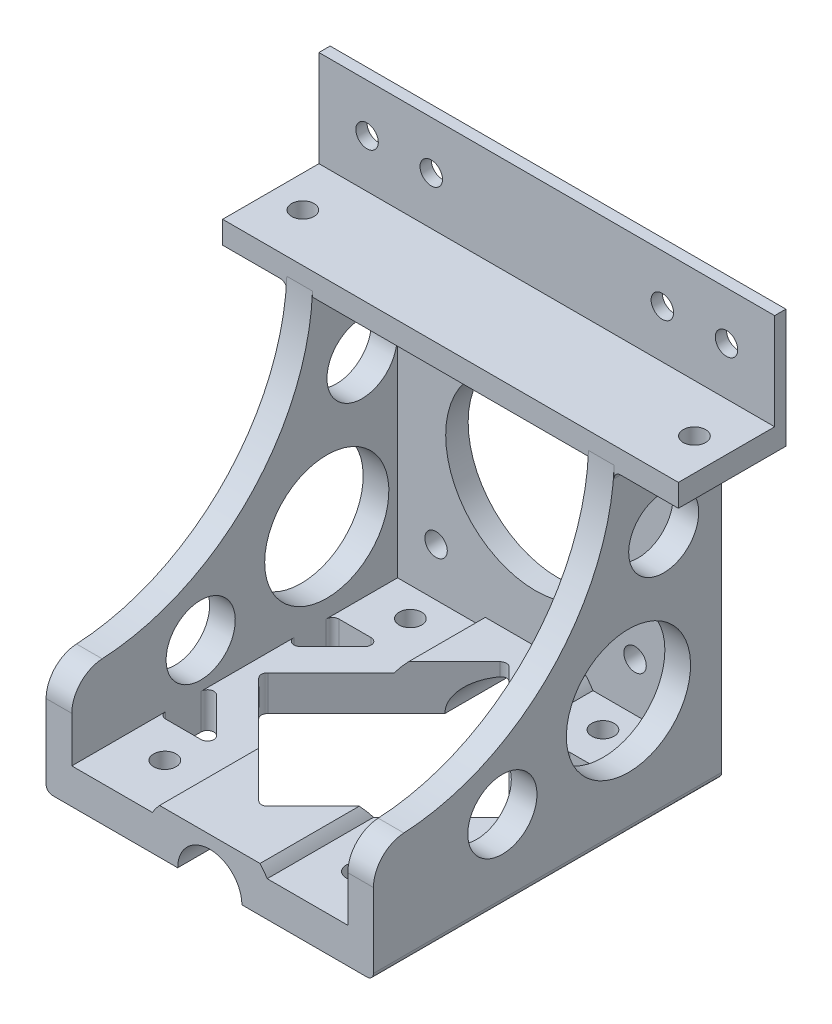
SolidWorks part; units mm, degrees
ref_plane "Front Plane" through (0, 0, 0) normal (0, 0, 1) x (1, 0, 0)
ref_plane "Top Plane" through (0, 0, 0) normal (0, 1, 0) x (1, 0, 0)
ref_plane "Right Plane" through (0, 0, 0) normal (1, 0, 0) x (0, 0, -1)
sketch "Sketch1" plane through (0, 0, 0) normal (0, 0, 1) x (1, 0, 0)
  line L1 (-51.9324, 28.7717) -> (-0.9324, 28.7717)
  line L2 (-51.9324, 28.7717) -> (-51.9324, -24.7283)
  line L3 (-51.9324, -24.7283) -> (-0.9324, -24.7283)
  line L4 (-0.9324, 28.7717) -> (-0.9324, -24.7283)
  dimension "D1" = 51
  dimension "D2" = 53.5
extrude "Boss-Extrude1" add sketch "Sketch1" along normal blind 54.25
sketch "Sketch2" plane through (0, 0, 54.25) normal (0, 0, 1) x (1, 0, 0)
  line L0 (-0.9324, -24.7283) -> (-0.9324, 28.7717) construction
  line L1 (-47.9324, -17.7283) -> (-4.9324, -17.7283)
  line L2 (-47.9324, -17.7283) -> (-47.9324, 25.2717)
  line L3 (-47.9324, 25.2717) -> (-4.9324, 25.2717)
  line L4 (-4.9324, -17.7283) -> (-4.9324, 25.2717)
  line L6 (-51.9324, -24.7283) -> (-0.9324, -24.7283) construction
  dimension "D1" = 43
  dimension "D2" = 43
  dimension "D3" = 4
  dimension "D4" = 7
extrude "Cut-Extrude1" cut sketch "Sketch2" against normal offset from surface (50.75 mm away) 3.5 up to face at (-26.4324, 2.0217, 0)
sketch "Sketch3" plane through (0, 0, 54.25) normal (0, 0, 1) x (1, 0, 0)
  line L0 (-0.9324, 28.7717) -> (-51.9324, 28.7717) construction
  line L1 (-47.9324, 25.2717) -> (-4.9324, 25.2717)
  line L2 (-47.9324, 25.2717) -> (-47.9324, 28.7717)
  line L3 (-47.9324, 28.7717) -> (-4.9324, 28.7717)
  line L4 (-4.9324, 25.2717) -> (-4.9324, 28.7717)
extrude "Cut-Extrude2" cut sketch "Sketch3" against normal offset from surface (37.5 mm away) 16.75 up to face at (-26.4324, 2.0217, 0)
sketch "Sketch4" plane through (-51.9324, 0, 0) normal (-1, 0, 0) x (0, 0, 1)
  line L0 (16.75, 25.2717) -> (16.75, 28.7717) construction
  line L1 (54.25, 28.7717) -> (54.25, -24.7283) construction
  line L3 (16.75, 28.7717) -> (54.25, 28.7717)
  line L4 (54.25, 28.7717) -> (54.25, -7.0747)
  arc A0 (16.75, 28.7717) -> (54.25, -7.0747) centre (51.3457, 27.4252) ccw
extrude "Cut-Extrude3" cut sketch "Sketch4" against normal blind 76
sketch "Sketch5" plane through (-51.9324, 0, 0) normal (-1, 0, 0) x (0, 0, 1)
  circle A0 centre (14.5252, -6.808) radius 9.6731
  circle A1 centre (34.169, -12.2977) radius 5.3908
  circle A2 centre (9.0356, 13.1664) radius 5.4569
extrude "Cut-Extrude4" cut sketch "Sketch5" against normal blind 76
sketch "Sketch6" plane through (0, 0, 3.5) normal (0, 0, 1) x (1, 0, 0)
  line L0 (-4.9324, 25.2717) -> (-47.9324, -17.7283) construction
  line L1 (-4.9324, -17.7283) -> (-47.9324, 25.2717) construction
  circle A0 centre (-26.4324, 3.7717) radius 14
  circle A1 centre (-10.9324, 19.2717) radius 1.75
  circle A2 centre (-41.9324, 19.2717) radius 1.75
  circle A3 centre (-41.9324, -11.7283) radius 1.75
  circle A4 centre (-10.9324, -11.7283) radius 1.75
  dimension "D2" = 28
  dimension "D3" = 3.5
  dimension "D1" = 31
extrude "Cut-Extrude5" cut sketch "Sketch6" against normal blind 76
sketch "Sketch7" plane through (0, 0, 0) normal (0, 0, -1) x (-1, 0, 0)
  line L0 (51.9324, -24.7283) -> (0.9324, -24.7283) construction
  circle A0 centre (26.4324, -24.7283) radius 5
  dimension "D1" = 10
extrude "Cut-Extrude6" cut sketch "Sketch7" against normal blind 76
sketch "Sketch8" plane through (0, -24.7283, 0) normal (0, -1, 0) x (1, 0, 0)
  line L0 (-26.4324, 54.25) -> (-26.4324, 0) construction
  line L1 (-21.4324, 54.25) -> (-31.4324, 54.25) construction
  line L2 (-31.4324, 0) -> (-21.4324, 0) construction
  line L3 (-26.4324, 46.625) -> (-6.9324, 27.125)
  line L4 (-4.9324, 3.5) -> (-4.9324, 54.25) construction
  line L5 (-6.9324, 27.125) -> (-26.4324, 7.625)
  line L7 (-26.4324, 7.625) -> (-45.9324, 27.125)
  line L8 (-45.9324, 27.125) -> (-26.4324, 46.625)
  line L9 (-47.9324, 3.5) -> (-47.9324, 54.25) construction
  line L10 (-26.4324, 7.625) -> (-4.9324, 7.625) construction
  line L11 (-26.4324, 7.625) -> (-47.9324, 7.625) construction
  line L12 (-26.4324, 46.625) -> (-47.9324, 46.625) construction
  line L13 (-26.4324, 46.625) -> (-4.9324, 46.625) construction
  line L14 (-13.3613, 40.625) -> (-4.9324, 40.625)
  line L15 (-4.9324, 40.625) -> (-4.9324, 32.1961)
  line L16 (-4.9324, 32.1961) -> (-13.3613, 40.625)
  line L17 (-4.9324, 13.625) -> (-13.3613, 13.625)
  line L18 (-13.3613, 13.625) -> (-4.9324, 22.0539)
  line L19 (-4.9324, 22.0539) -> (-4.9324, 13.625)
  line L20 (-47.9324, 13.625) -> (-39.5034, 13.625)
  line L21 (-39.5034, 13.625) -> (-47.9324, 22.0539)
  line L22 (-47.9324, 22.0539) -> (-47.9324, 13.625)
  line L23 (-47.9324, 40.625) -> (-39.0071, 40.625)
  line L24 (-39.0071, 40.625) -> (-47.9324, 31.6997)
  line L25 (-47.9324, 31.6997) -> (-47.9324, 40.625)
  line L26 (-6.9324, 0) -> (-6.9324, 54.25) construction
  line L27 (-21.4324, 0) -> (-0.9324, 0) construction
  line L28 (-21.4324, 54.25) -> (-0.9324, 54.25) construction
  line L29 (-45.9324, 54.25) -> (-45.9324, 0) construction
  line L30 (-51.9324, 54.25) -> (-31.4324, 54.25) construction
  line L31 (-51.9324, 0) -> (-31.4324, 0) construction
  line L32 (-0.9324, 54.25) -> (-0.9324, 0) construction
  dimension "D1" = 7.625
  dimension "D2" = 45
  dimension "D3" = 6
  dimension "D4" = 45
  dimension "D5" = 5
  dimension "D6" = 6
  dimension "D7" = 5
  dimension "D8" = 5
  dimension "D9" = 6
extrude "Cut-Extrude7" cut sketch "Sketch8" against normal blind 27
fillet "Fillet2" radius 1 16 edges at (-47.9324, -21.2283, 31.6997) (-4.9324, -21.2283, 32.1961) (-4.9324, -21.2283, 22.0539) (-47.9324, -21.2283, 22.0539) (-13.3613, -21.2283, 13.625) (-39.5034, -21.2283, 13.625) (-26.4324, -18.7283, 7.625) (-4.9324, -21.2283, 13.625) (-47.9324, -21.2283, 13.625) (-45.9324, -21.2283, 27.125) (-6.9324, -21.2283, 27.125) (-4.9324, -21.2283, 40.625) (-47.9324, -21.2283, 40.625) (-39.0071, -21.2283, 40.625) (-13.3613, -21.2283, 40.625) (-26.4324, -18.7283, 46.625)
sketch "Sketch12" plane through (0, -24.7283, 0) normal (0, -1, 0) x (1, 0, 0)
  line L1 (-47.9324, 54.25) -> (-4.9324, 54.25) construction
  line L2 (-21.4324, 54.25) -> (-31.4324, 54.25) construction
  line L4 (-10.9471, 13.625) -> (-5.9324, 13.625) construction
  line L5 (-5.9324, 40.625) -> (-10.9471, 40.625) construction
  circle A0 centre (-11.4324, 46.25) radius 1.75
  circle A1 centre (-41.4324, 46.25) radius 1.75
  circle A2 centre (-11.4324, 8) radius 1.75
  circle A3 centre (-41.4324, 8) radius 1.75
  point P10 (-26.4324, 54.25)
  point P13 (-26.4324, 54.25)
  dimension "D1" = 5.625
  dimension "D2" = 15
  dimension "D3" = 15
  dimension "D4" = 5.625
extrude "Cut-Extrude8" cut sketch "Sketch12" against normal blind 15
sketch "Sketch13" plane through (-51.9324, 0, 0) normal (-1, 0, 0) x (0, 0, 1)
  line L0 (3.5, 25.2717) -> (16.75, 25.2717) construction
  line L1 (0, 28.7717) -> (16.75, 28.7717)
  line L2 (0, 28.7717) -> (0, 25.2717)
  line L3 (0, 25.2717) -> (16.75, 25.2717)
  line L4 (16.75, 28.7717) -> (16.75, 25.2717)
  line L5 (16.75, 28.7717) -> (0, 28.7717) construction
  arc A0 (16.75, 28.7717) -> (54.25, -7.0747) centre (51.3457, 27.4252) ccw construction
extrude "Boss-Extrude4" add sketch "Sketch13" along normal blind 10 and the other way offset from surface (61 mm away) 10 other way up to face at (-0.9324, 7.7095, 9.0356)
sketch "Sketch14" plane through (0, 28.7717, 0) normal (0, 1, 0) x (1, 0, 0)
  line L0 (9.0676, 0) -> (9.0676, -16.75) construction
  line L1 (-61.9324, 0) -> (9.0676, 0)
  line L2 (-61.9324, 0) -> (-61.9324, -1.75)
  line L3 (-61.9324, -1.75) -> (9.0676, -1.75)
  line L4 (9.0676, 0) -> (9.0676, -1.75)
  dimension "D1" = 1.75
extrude "Boss-Extrude5" add sketch "Sketch14" along normal blind 15
sketch "Sketch15" plane through (0, 25.2717, 0) normal (0, -1, 0) x (1, 0, 0)
  line L0 (4.0676, 0) -> (4.0676, 16.75) construction
  line L1 (9.0676, 0) -> (-0.9324, 0) construction
  line L2 (9.0676, 16.75) -> (-0.9324, 16.75) construction
  line L3 (9.0676, 9.25) -> (-61.9324, 9.25) construction
  line L6 (-56.9324, 16.75) -> (-56.9324, 0) construction
  line L7 (-51.9324, 16.75) -> (-61.9324, 16.75) construction
  line L8 (-51.9324, 0) -> (-61.9324, 0) construction
  circle A0 centre (-56.9324, 9.25) radius 1.75
  circle A1 centre (4.0676, 9.25) radius 1.75
  dimension "D1" = 3.5
  dimension "D2" = 7.5
extrude "Cut-Extrude9" cut sketch "Sketch15" against normal blind 10
sketch "Sketch16" plane through (0, 0, 0) normal (0, 0, -1) x (-1, 0, 0)
  line L0 (-9.0676, 43.7717) -> (61.9324, 43.7717) construction
  line L1 (61.9324, 43.7717) -> (61.9324, 25.2717) construction
  line L2 (-9.0676, 25.2717) -> (-9.0676, 43.7717) construction
  circle A0 centre (54.4324, 36.2717) radius 1.75
  circle A1 centre (-1.5676, 36.2717) radius 1.75
  circle A2 centre (44.4324, 36.2717) radius 1.75
  circle A3 centre (8.4324, 36.2717) radius 1.75
  dimension "D1" = 3.5
  dimension "D2" = 7.5
  dimension "D3" = 7.5
  dimension "D4" = 7.5
  dimension "D5" = 10
  dimension "D6" = 10
  dimension "D7" = 7.5
  dimension "D8" = 7.5
extrude "Cut-Extrude10" cut sketch "Sketch16" against normal blind 10
sketch "Sketch17" plane through (0, 0, 54.25) normal (0, 0, 1) x (1, 0, 0)
  line L0 (-17.4881, -19.2283) -> (-4.9324, -19.2283)
  line L2 (-4.9324, -24.7283) -> (-4.9324, -17.7283) construction
  line L3 (-4.9324, -19.2283) -> (-4.9324, -17.7283)
  line L5 (-4.9324, -17.7283) -> (-18.6061, -17.7283)
  line L7 (-47.9324, -17.7283) -> (-4.9324, -17.7283) construction
  line L8 (-35.3766, -19.2283) -> (-47.9324, -19.2283)
  line L10 (-47.9324, -17.7283) -> (-47.9324, -24.7283) construction
  line L11 (-47.9324, -19.2283) -> (-47.9324, -17.7283)
  line L12 (-47.9324, -17.7283) -> (-34.2586, -17.7283)
  line L13 (-21.4324, -24.7283) -> (-0.9324, -24.7283) construction
  arc A0 (-17.4881, -19.2283) -> (-18.6061, -17.7283) centre (-26.4324, -24.7283) ccw
  arc A1 (-34.2586, -17.7283) -> (-35.3766, -19.2283) centre (-26.4324, -24.7283) ccw
  dimension "D1" = 21
  dimension "D2" = 5.5
extrude "Cut-Extrude11" cut sketch "Sketch17" against normal up to surface (50.75 mm away) up to face at (-9.1824, -11.7283, 3.5)
fillet "Fillet3" radius 5 2 edges at (-49.9324, -7.0747, 54.25) (-2.9324, -7.0747, 54.25)
fillet "Fillet4" radius 1 4 edges at (-0.9324, 25.2717, 8.375) (-51.9324, 25.2717, 8.375) (-0.9324, -24.7283, 27.125) (-51.9324, -24.7283, 27.125)
sketch "Sketch19" plane through (0, -24.7283, 0) normal (0, 1, 0) x (1, 0, 0)
  line L0 (-4.9324, -16.75) -> (-4.9324, -49.5145) construction
  line L1 (-44.4324, -9.7321) -> (-41.4324, -11.4641)
  line L2 (-41.4324, -11.4641) -> (-38.4324, -9.7321)
  line L3 (-38.4324, -9.7321) -> (-38.4324, -6.2679)
  line L4 (-38.4324, -6.2679) -> (-41.4324, -4.5359)
  line L5 (-41.4324, -4.5359) -> (-44.4324, -6.2679)
  line L6 (-44.4324, -6.2679) -> (-44.4324, -9.7321)
  line L7 (-11.4324, -4.5359) -> (-14.4324, -6.2679)
  line L8 (-14.4324, -6.2679) -> (-14.4324, -9.7321)
  line L9 (-14.4324, -9.7321) -> (-11.4324, -11.4641)
  line L10 (-11.4324, -11.4641) -> (-8.4324, -9.7321)
  line L11 (-8.4324, -9.7321) -> (-8.4324, -6.2679)
  line L12 (-8.4324, -6.2679) -> (-11.4324, -4.5359)
  line L13 (-38.4324, -47.9821) -> (-38.4324, -44.5179)
  line L14 (-38.4324, -44.5179) -> (-41.4324, -42.7859)
  line L15 (-41.4324, -42.7859) -> (-44.4324, -44.5179)
  line L16 (-44.4324, -44.5179) -> (-44.4324, -47.9821)
  line L17 (-44.4324, -47.9821) -> (-41.4324, -49.7141)
  line L18 (-41.4324, -49.7141) -> (-38.4324, -47.9821)
  line L19 (-8.4324, -47.9821) -> (-8.4324, -44.5179)
  line L20 (-8.4324, -44.5179) -> (-11.4324, -42.7859)
  line L21 (-11.4324, -42.7859) -> (-14.4324, -44.5179)
  line L22 (-14.4324, -44.5179) -> (-14.4324, -47.9821)
  line L23 (-14.4324, -47.9821) -> (-11.4324, -49.7141)
  line L24 (-11.4324, -49.7141) -> (-8.4324, -47.9821)
  circle A0 centre (-41.4324, -8) radius 3 construction
  circle A1 centre (-11.4324, -8) radius 3 construction
  circle A2 centre (-41.4324, -46.25) radius 3 construction
  circle A3 centre (-11.4324, -46.25) radius 3 construction
  dimension "D1" = 6
extrude "Cut-Extrude12" cut sketch "Sketch19" along normal blind 3
